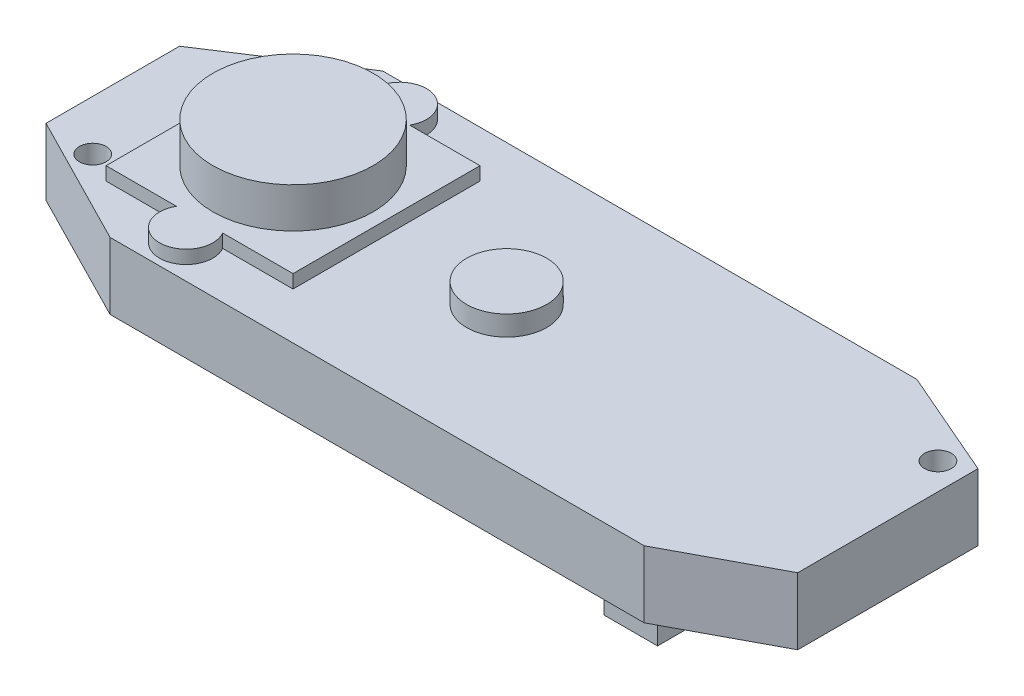
SolidWorks part; units mm, degrees
ref_plane "Спереди" through (0, 0, 0) normal (0, 0, 1) x (1, 0, 0)
ref_plane "Сверху" through (0, 0, 0) normal (0, 1, 0) x (1, 0, 0)
ref_plane "Справа" through (0, 0, 0) normal (1, 0, 0) x (0, 0, -1)
sketch "Эскиз1" plane through (0, 0, 0) normal (0, 1, 0) x (1, 0, 0)
  line L0 (-29.798, -5) -> (-29.798, 5)
  line L1 (-29.798, 5) -> (-20.5784, 11)
  line L2 (-20.5784, 11) -> (19.4216, 11)
  line L3 (19.4216, 11) -> (27.5, 7.5)
  line L4 (27.5, 7.5) -> (27.5, -6)
  line L5 (27.5, -6) -> (20, -10)
  line L6 (20, -10) -> (-20, -10)
  line L7 (-20, -10) -> (-29.798, -5)
  point P9 (-29.798, 0)
  point P10 (0, -10)
  dimension "D1" = 10
  dimension "D2" = 13.5
  dimension "D3" = 8.5
  dimension "D4" = 4
  dimension "D5" = 40
  dimension "D6" = 11
  dimension "D7" = 5
  dimension "D8" = 6
  dimension "D9" = 11
  dimension "D10" = 40
extrude "Бобышка-Вытянуть1" add sketch "Эскиз1" along normal blind 5
sketch "Эскиз2" plane through (0, 5, 0) normal (0, 1, 0) x (1, 0, 0)
  line L0 (-29.798, 5) -> (-29.798, -5) construction
  line L1 (-23.798, 7.5) -> (-18.53, 7.5)
  line L2 (-23.798, 7.5) -> (-23.798, -6.5)
  line L3 (-23.798, -6.5) -> (-18.53, -6.5)
  line L4 (-9.798, 7.5) -> (-9.798, -6.5)
  line L6 (-23.798, 7.5) -> (-9.798, -6.5) construction
  line L7 (-1000, 0.5) -> (49000, 0.5) construction
  line L8 (-23.798, -6.5) -> (-9.798, 7.5) construction
  line L9 (-15.0659, 7.5) -> (-9.798, 7.5)
  line L10 (-15.0659, -6.5) -> (-9.798, -6.5)
  line L11 (19.4216, 11) -> (-20.5784, 11) construction
  arc A0 (-15.0659, 7.5) -> (-18.53, 7.5) centre (-16.798, 8.5) ccw
  arc A1 (-15.0659, -6.5) -> (-18.53, -6.5) centre (-16.798, -7.5) cw
  point P11 (-16.798, 0.5)
  dimension "D3" = 4
  dimension "D1" = 6
  dimension "D2" = 14
  dimension "D4" = 1
  dimension "D5" = 3.5
extrude "Бобышка-Вытянуть2" add sketch "Эскиз2" along normal blind 1
sketch "Эскиз3" plane through (0, 6, 0) normal (0, 1, 0) x (1, 0, 0)
  line L0 (-16.798, -989.5) -> (-16.798, 49010.5) construction
  line L1 (-1023.798, 0.5) -> (48976.202, 0.5) construction
  line L2 (-23.798, 7.5) -> (-23.798, -6.5) construction
  arc A0 (-15.0659, 7.5) -> (-18.53, 7.5) centre (-16.798, 8.5) ccw construction
  circle A1 centre (-16.798, 0.5) radius 6
  point P6 (-16.798, 10.5)
  point P11 (-23.798, 0.5)
  point P13 (-16.798, 0.5)
  dimension "D1" = 12
extrude "Бобышка-Вытянуть3" add sketch "Эскиз3" along normal blind 3
sketch "Эскиз4" plane through (0, 5, 0) normal (0, 1, 0) x (1, 0, 0)
  line L0 (-9.798, -6.5) -> (-9.798, 7.5) construction
  line L1 (19.4216, 11) -> (-20.5784, 11) construction
  circle A0 centre (-0.798, 0.5) radius 3
  dimension "D2" = 6
  dimension "D1" = 9
  dimension "D3" = 10.5
extrude "Бобышка-Вытянуть4" add sketch "Эскиз4" along normal blind 1.5
sketch "Эскиз6" plane through (0, 0, 0) normal (0, -1, 0) x (1, 0, 0)
  line L0 (27.5, 6) -> (27.5, -7.5) construction
  line L1 (19.5, 8.5) -> (15.5, 8.5)
  line L2 (19.5, 8.5) -> (19.5, 2.5)
  line L3 (19.5, 2.5) -> (15.5, 2.5)
  line L4 (15.5, 8.5) -> (15.5, 2.5)
  line L5 (-20, 10) -> (20, 10) construction
  dimension "D1" = 8
  dimension "D2" = 4
  dimension "D3" = 6
  dimension "D4" = 1.5
extrude "Бобышка-Вытянуть5" add sketch "Эскиз6" along normal blind 2.5
sketch "Эскиз7" plane through (0, 5, 0) normal (0, 1, 0) x (1, 0, 0)
  line L0 (-29.798, 5) -> (-29.798, -5) construction
  line L1 (27.5, -6) -> (27.5, 7.5) construction
  circle A0 centre (-26.048, -5.25) radius 1
  circle A1 centre (25.5, 6.5) radius 1
  dimension "D3" = 2
  dimension "D1" = 3.75
  dimension "D2" = 0.25
  dimension "D4" = 2
  dimension "D5" = 1
extrude "Вырез-Вытянуть1" cut sketch "Эскиз7" against normal blind 5
